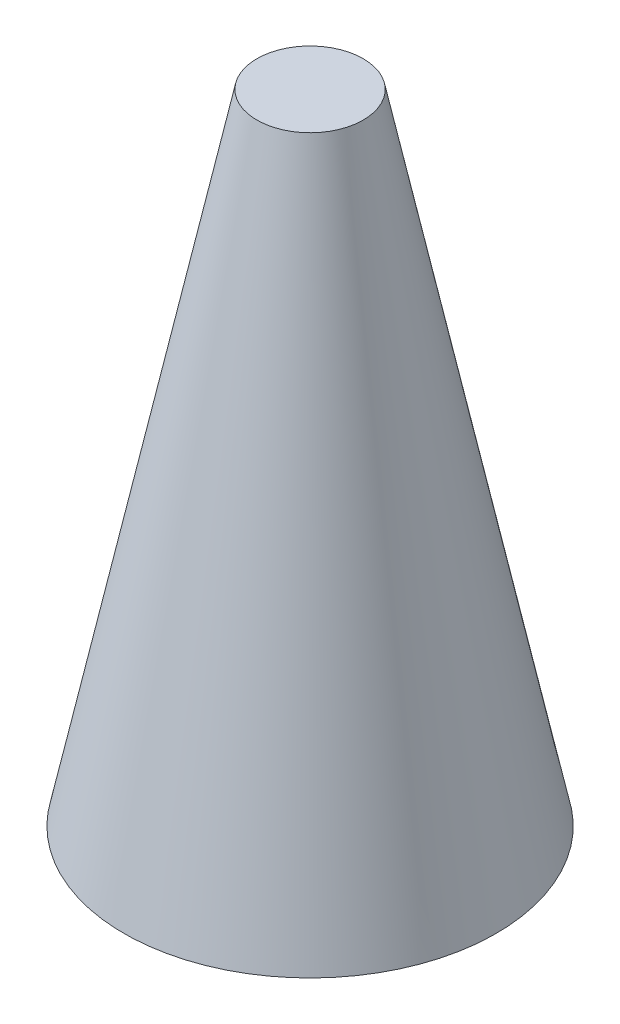
SolidWorks part; units mm, degrees
ref_plane "Front Plane" through (0, 0, 0) normal (0, 0, 1) x (1, 0, 0)
ref_plane "Top Plane" through (0, 0, 0) normal (0, 1, 0) x (1, 0, 0)
ref_plane "Right Plane" through (0, 0, 0) normal (1, 0, 0) x (0, 0, -1)
sketch "Sketch1" plane through (0, 0, 0) normal (0, 1, 0) x (1, 0, 0)
  circle A0 centre (0, 0) radius 44.45
  dimension "D1" = 88.9
ref_plane "Plane1" through (0, 152.4, 0) normal (0, 1, 0) x (1, 0, 0)
sketch "Sketch2" plane through (0, 152.4, 0) normal (0, 1, 0) x (1, 0, 0)
  circle A0 centre (0, 0) radius 12.7
  dimension "D1" = 25.4
loft "Loft1" add profiles "Sketch1", "Sketch2"
sketch "Sketch3" plane through (0, 0, 0) normal (0, 0, 1) x (1, 0, 0)
  line L0 (0, 0) -> (0, 155.3744) construction
  text T0 "<b>AVIONICS</b>" font "Century Gothic" height 12.7
extrude "Cut-Extrude1" cut sketch "Sketch3" against normal mid plane 1.27
